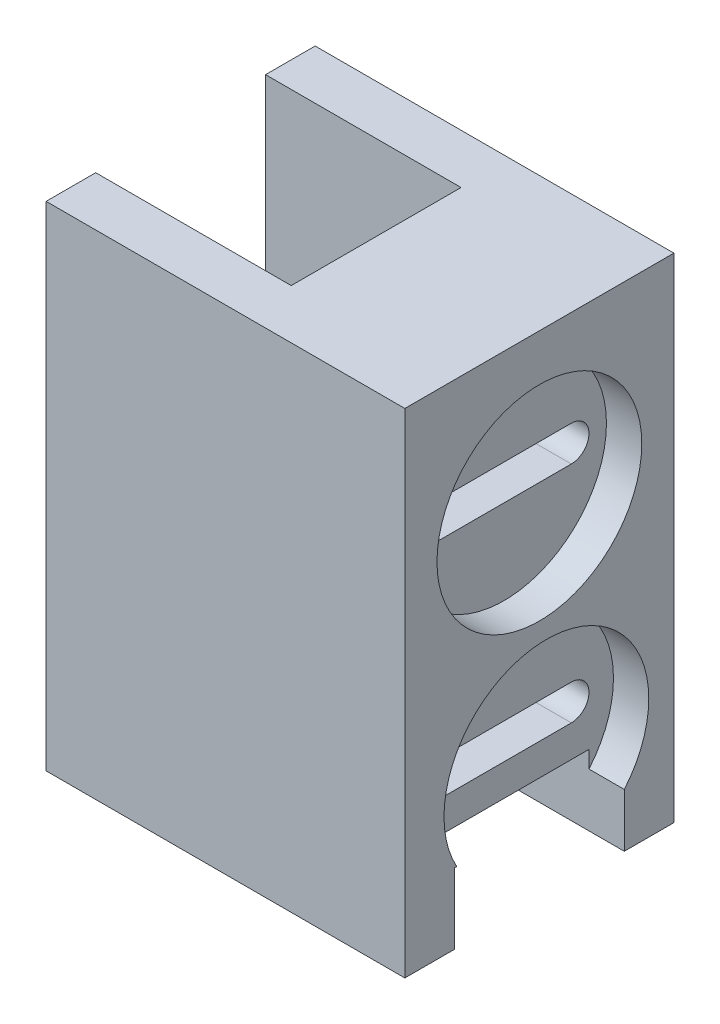
SolidWorks part; units mm, degrees
ref_plane "Front Plane" through (0, 0, 0) normal (0, 0, 1) x (1, 0, 0)
ref_plane "Top Plane" through (0, 0, 0) normal (0, 1, 0) x (1, 0, 0)
ref_plane "Right Plane" through (0, 0, 0) normal (1, 0, 0) x (0, 0, -1)
sketch "Sketch1" plane through (0, 0, 0) normal (0, 1, 0) x (1, 0, 0)
  line L1 (0, 0) -> (10.16, 0)
  line L2 (0, 0) -> (0, 7.62)
  line L3 (0, 7.62) -> (10.16, 7.62)
  line L4 (10.16, 0) -> (10.16, 7.62)
  dimension "D1" = 7.62
  dimension "D2" = 10.16
extrude "Boss-Extrude1" add sketch "Sketch1" along normal blind 13.97
sketch "Sketch2" plane through (10.16, 0, 0) normal (1, 0, 0) x (0, 0, -1)
  line L0 (0, 0) -> (7.62, 0) construction
  circle A0 centre (4.0086, 3.4) radius 2.9
  circle A1 centre (3.81, 9.75) radius 2.9
  dimension "D1" = 5.8
  dimension "D2" = 5.8
  dimension "D3" = 3.4
  dimension "D4" = 6.35
extrude "Cut-Extrude1" cut sketch "Sketch2" against normal blind 1
sketch "Sketch3" plane through (10.16, 0, 0) normal (1, 0, 0) x (0, 0, -1)
  line L0 (1.905, 3.4) -> (5.715, 3.4) construction
  line L1 (1.905, 3.9) -> (5.715, 3.9)
  line L2 (1.905, 2.9) -> (5.715, 2.9)
  line L3 (1.905, 9.75) -> (5.715, 9.75) construction
  line L4 (1.905, 10.25) -> (5.715, 10.25)
  line L5 (1.905, 9.25) -> (5.715, 9.25)
  line L8 (0, 13.97) -> (7.62, 13.97) construction
  line L9 (3.81, 13.97) -> (3.81, 0)
  line L10 (0, 0) -> (7.62, 0) construction
  line L11 (1.405, 3.4) -> (6.215, 3.4)
  line L12 (1.405, 0) -> (6.215, 0)
  line L13 (1.405, 0) -> (1.405, 2)
  line L14 (1.405, 2) -> (6.215, 2)
  line L15 (6.215, 0) -> (6.215, 2)
  arc A0 (1.905, 3.9) -> (1.905, 2.9) centre (1.905, 3.4) ccw
  arc A1 (5.715, 2.9) -> (5.715, 3.9) centre (5.715, 3.4) ccw
  arc A2 (1.905, 10.25) -> (1.905, 9.25) centre (1.905, 9.75) ccw
  arc A3 (5.715, 9.25) -> (5.715, 10.25) centre (5.715, 9.75) ccw
  point P3 (3.81, 3.4)
  point P8 (3.81, 9.75)
  circle M2 centre (4.0086, 3.4) radius 2.9
  line M3 (0, 0) -> (7.62, 0)
  dimension "D1" = 1
  dimension "D2" = 1
  dimension "D3" = 3.81
  dimension "D4" = 3.81
  dimension "D5" = 2
extrude "Cut-Extrude2" cut sketch "Sketch3" against normal up to next contours L4 A2 L5 L9 | L5 A3 L4 L9 | L1 A0 L2 L9 | L2 A1 L1 L9 | L11 A1 L1 L9 | L11 A0 L2 L9 | L14 L13 L9 M3 M2 | L14 L9 M2 | L15 L14 L9 M2 | L15 L9 M3 M2
sketch "Sketch5" plane through (0, 0, 0) normal (-1, 0, 0) x (0, 0, 1)
  line L0 (-7.62, 13.97) -> (0, 13.97) construction
  line L1 (-6.215, 9.75) -> (-1.405, 9.75)
  line L2 (-6.215, 9.75) -> (-6.215, 13.97)
  line L3 (-6.215, 13.97) -> (-1.405, 13.97)
  line L4 (-1.405, 9.75) -> (-1.405, 13.97)
  arc A0 (-5.715, 10.25) -> (-5.715, 9.25) centre (-5.715, 9.75) ccw construction
extrude "Cut-Extrude4" cut sketch "Sketch5" against normal blind 5.5372
sketch "Sketch6" plane through (0, 0, 0) normal (-1, 0, 0) x (0, 0, 1)
  line L0 (-1.405, 13.97) -> (-6.215, 13.97) construction
  line L1 (-6.215, 3.4) -> (-1.405, 3.4)
  line L2 (-6.215, 3.4) -> (-6.215, 13.97)
  line L3 (-6.215, 13.97) -> (-1.405, 13.97)
  line L4 (-1.405, 3.4) -> (-1.405, 13.97)
  line L5 (-1.405, 13.97) -> (0, 13.97) construction
  arc A0 (-5.715, 3.9) -> (-5.715, 2.9) centre (-5.715, 3.4) ccw construction
extrude "Cut-Extrude6" cut sketch "Sketch6" against normal blind 2.9972
sketch "Sketch7" plane through (0, 0, 0) normal (-1, 0, 0) x (0, 0, 1)
  line L2 (-6.215, 3.4) -> (-1.405, 3.4)
  line L3 (-6.215, 3.4) -> (-6.215, 0)
  line L4 (-6.215, 0) -> (-1.405, 0)
  line L5 (-1.405, 3.4) -> (-1.405, 0)
extrude "Cut-Extrude7" cut sketch "Sketch7" against normal blind 5.5372
